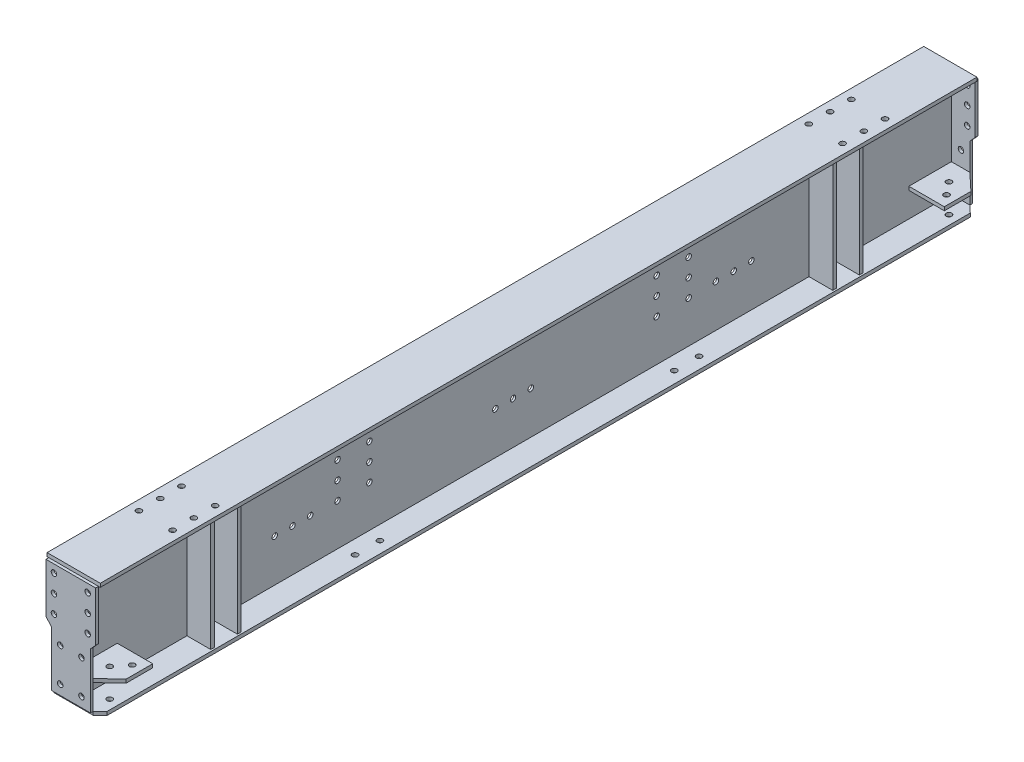
SolidWorks part; units mm, degrees
ref_plane "前视基准面" through (0, 0, 0) normal (0, 0, 1) x (1, 0, 0)
ref_plane "上视基准面" through (0, 0, 0) normal (0, 1, 0) x (1, 0, 0)
ref_plane "右视基准面" through (0, 0, 0) normal (1, 0, 0) x (0, 0, -1)
sketch "草图1" plane through (0, 0, 0) normal (0, 0, 1) x (1, 0, 0)
  line L0 (0, 0) -> (50000, 0) construction
  line L1 (0, 0) -> (0, 50000) construction
  line L2 (-150, 332.5) -> (150, 332.5)
  line L3 (150, 332.5) -> (150, 312.5)
  line L4 (150, 312.5) -> (6, 312.5)
  line L5 (6, 312.5) -> (6, -312.5)
  line L6 (6, -312.5) -> (150, -312.5)
  line L7 (150, -312.5) -> (150, -332.5)
  line L8 (150, -332.5) -> (-150, -332.5)
  line L9 (-150, -332.5) -> (-150, -312.5)
  line L10 (-150, -312.5) -> (-6, -312.5)
  line L11 (-6, -312.5) -> (-6, 312.5)
  line L12 (-6, 312.5) -> (-150, 312.5)
  line L13 (-150, 312.5) -> (-150, 332.5)
  dimension "D1" = 20
  dimension "D2" = 12
  dimension "D3" = 665
  dimension "D4" = 300
extrude "拉伸1" add sketch "草图1" along normal blind 2472
sketch "草图2" plane through (0, 0, 2472) normal (0, 0, 1) x (1, 0, 0)
  line L0 (-1000, 0) -> (49000, 0) construction
  line L1 (0, -1000) -> (0, 49000) construction
  line L2 (-140, 32.5) -> (-140, 312.5)
  line L3 (-150, 312.5) -> (-6, 312.5) construction
  line L4 (-140, 32.5) -> (-110, -0.5)
  line L5 (-140, 312.5) -> (140, 312.5)
  line L6 (-110, -0.5) -> (-110, -312.5)
  line L7 (-150, -332.5) -> (150, -332.5) construction
  line L8 (150, 332.5) -> (-150, 332.5) construction
  line L10 (-6, -312.5) -> (-150, -312.5) construction
  line L11 (-110, -312.5) -> (110, -312.5)
  line L12 (110, -0.5) -> (110, -312.5)
  line L13 (140, 32.5) -> (110, -0.5)
  line L14 (140, 32.5) -> (140, 312.5)
  point P7 (0, -312.5)
  point P18 (0, -332.5)
  point P21 (0, 332.5)
  point P23 (0, 312.5)
  dimension "D1" = 312
  dimension "D2" = 33
  dimension "D3" = 280
  dimension "D4" = 140
  dimension "D5" = 110
extrude "拉伸2" add sketch "草图2" along normal blind 16 separate body
sketch "草图3" plane through (0, 0, 2488) normal (0, 0, 1) x (1, 0, 0)
  line L0 (-1000, 0) -> (49000, 0) construction
  line L1 (0, -1000) -> (0, 49000) construction
  line L3 (-150, 312.5) -> (-6, 312.5) construction
  circle A0 centre (-95, 267.5) radius 15.5
  circle A1 centre (-95, 167.5) radius 15.5
  circle A2 centre (-95, 67.5) radius 15.5
  circle A3 centre (-60, -67.5) radius 15.5
  circle A4 centre (-60, -257.5) radius 15.5
  circle A5 centre (60, -257.5) radius 15.5
  circle A6 centre (60, -67.5) radius 15.5
  circle A7 centre (95, 67.5) radius 15.5
  circle A8 centre (95, 167.5) radius 15.5
  circle A9 centre (95, 267.5) radius 15.5
  dimension "D1" = 31
  dimension "D2" = 95
  dimension "D3" = 45
  dimension "D4" = 100
  dimension "D5" = 135
  dimension "D6" = 190
  dimension "D7" = 60
extrude "拉伸3" cut sketch "草图3" against normal through all
sketch "草图4" plane through (0, 332.5, 0) normal (0, 1, 0) x (1, 0, 0)
  line L0 (0, -1000) -> (0, 49000) construction
  line L1 (150, -2472) -> (-150, -2472) construction
  line L3 (-95, -2009) -> (-95, -1889) construction
  circle A0 centre (-95, -2009) radius 15.5
  circle A1 centre (-95, -1889) radius 15.5
  circle A2 centre (-95, -1769) radius 15.5
  circle A3 centre (95, -2009) radius 15.5
  circle A4 centre (95, -1889) radius 15.5
  circle A5 centre (95, -1769) radius 15.5
  dimension "D1" = 31
  dimension "D2" = 463
  dimension "D3" = 95
  dimension "D4" = 120
extrude "拉伸5" cut sketch "草图4" against normal blind 20
ref_plane "基准面1" through (0, -162.5, 0) normal (0, -1, 0) x (1, 0, 0)
sketch "草图6" plane through (0, -162.5, 0) normal (0, -1, 0) x (1, 0, 0)
  line L0 (0, -1000) -> (0, 49000) construction
  line L1 (-110, 2472) -> (-6, 2472)
  line L2 (-110, 2472) -> (-206, 2382)
  line L3 (-206, 2382) -> (-206, 2232)
  line L5 (-206, 2232) -> (-6, 2232)
  line L6 (-6, 2472) -> (-6, 0) construction
  line L7 (-6, 2232) -> (-6, 2472)
  line L8 (6, 2232) -> (6, 2472)
  line L9 (206, 2232) -> (6, 2232)
  line L10 (206, 2382) -> (206, 2232)
  line L11 (110, 2472) -> (206, 2382)
  line L12 (110, 2472) -> (6, 2472)
  dimension "D1" = 200
  dimension "D2" = 150
  dimension "D3" = 90
extrude "拉伸6" add sketch "草图6" along normal mid plane 20 separate body
sketch "草图7" plane through (0, -162.5, 0) normal (0, -1, 0) x (1, 0, 0)
  line L0 (0, -1000) -> (0, 49000) construction
  line L2 (-995.5174, 2488) -> (49004.4826, 2488) construction
  line L4 (-2000, 0) -> (-2000, 2488) construction
  line L6 (0, 2488) -> (-2362.8315, -451.3623) construction
  line L7 (-110, 2488) -> (110, 2488) construction
  circle A0 centre (-97.7382, 2366.4137) radius 15.5
  circle A1 centre (-154.1257, 2296.2677) radius 15.5
  circle A2 centre (154.1257, 2296.2677) radius 15.5
  circle A3 centre (97.7382, 2366.4137) radius 15.5
  dimension "D3" = 31
  dimension "D1" = 2488
  dimension "D2" = 2000
  dimension "D4" = 156
  dimension "D5" = 90
extrude "拉伸7" cut sketch "草图7" against normal mid plane 20
sketch "草图8" plane through (0, 312.5, 0) normal (0, -1, 0) x (1, 0, 0)
  line L0 (0, -1000) -> (0, 49000) construction
  line L1 (-95, 1889) -> (-95, 1769) construction
  line L2 (140, 1839) -> (-140, 1839)
  line L3 (-140, 1839) -> (-140, 1819)
  line L4 (-140, 1819) -> (140, 1819)
  line L5 (-1095, 1829) -> (48905, 1829) construction
  line L6 (140, 1839) -> (140, 1819)
  line L7 (140, 1689) -> (140, 1669)
  line L8 (-140, 1669) -> (140, 1669)
  line L9 (-140, 1689) -> (-140, 1669)
  line L10 (140, 1689) -> (-140, 1689)
  point P9 (0, 1839)
  point P14 (-95, 1829)
  point P16 (0, 1819)
  dimension "D1" = 140
  dimension "D2" = 20
  dimension "D3" = 150
  dimension "D4" = 20
  dimension "D5" = 280
extrude "拉伸8" add sketch "草图8" along normal blind 625
sketch "草图9" plane through (6, 0, 0) normal (1, 0, 0) x (0, 0, -1)
  line L0 (-2472, -332.5) -> (0, -332.5) construction
  line L2 (-900, -28.7712) -> (-900, -109.6678) construction
  line L3 (0, -312.5) -> (0, 312.5) construction
  line L4 (0, -88.5) -> (0, -58.5)
  line L5 (-2488, -312.5) -> (-2488, -0.5) construction
  circle A0 centre (-1344, -73.5) radius 15.5
  circle A1 centre (-1244, -73.5) radius 15.5
  circle A2 centre (-1144, -73.5) radius 15.5
  circle A3 centre (-990, -77.5) radius 15.5
  circle A4 centre (-990, 22.5) radius 15.5
  circle A5 centre (-990, 122.5) radius 15.5
  circle A6 centre (-810, 122.5) radius 15.5
  circle A7 centre (-810, 22.5) radius 15.5
  circle A8 centre (-810, -77.5) radius 15.5
  circle A9 centre (-100, -73.5) radius 15.5
  arc A10 (0, -58.5) -> (0, -88.5) centre (0, -73.5) ccw
  dimension "D1" = 31
  dimension "D5" = 31
  dimension "D10" = 31
  dimension "D13" = 15
  dimension "D2" = 259
  dimension "D3" = 1144
  dimension "D4" = 100
  dimension "D6" = 255
  dimension "D7" = 154
  dimension "D8" = 100
  dimension "D9" = 90
  dimension "D11" = 710
  dimension "D12" = 259
  dimension "D14" = 100
extrude "拉伸9" cut sketch "草图9" against normal blind 625
sketch "草图10" plane through (0, -312.5, 0) normal (0, 1, 0) x (1, 0, 0)
  line L1 (0, -1000) -> (0, 49000) construction
  line L2 (150, -2472) -> (150, 0) construction
  line L3 (-850, -900) -> (49150, -900) construction
  line L4 (150, 0) -> (-150, 0) construction
  line L6 (140, -2488) -> (-140, -2488) construction
  circle A0 centre (85, -970) radius 15.5
  circle A1 centre (85, -830) radius 15.5
  circle A2 centre (-85, -830) radius 15.5
  circle A3 centre (-85, -970) radius 15.5
  dimension "D1" = 31
  dimension "D2" = 1518
  dimension "D3" = 85
  dimension "D4" = 65
  dimension "D5" = 70
  dimension "D6" = 900
extrude "拉伸10" cut sketch "草图10" against normal blind 625
sketch "草图11" plane through (0, -312.5, 0) normal (0, 1, 0) x (1, 0, 0)
  line L0 (110, -2472) -> (150, -2472)
  line L3 (140, -2472) -> (-140, -2472) construction
  line L4 (150, -2472) -> (150, -2434.5)
  line L5 (150, -2434.5) -> (110, -2472)
  line L6 (-150, -2434.5) -> (-110, -2472)
  line L7 (-150, -2472) -> (-150, 0) construction
  line L8 (-110, -2472) -> (-206, -2382) construction
  line L9 (-110, -2472) -> (-150, -2472)
  line L10 (-150, -2472) -> (-150, -2434.5)
  line L11 (0, -1000) -> (0, 49000) construction
  circle A0 centre (-97.7382, -2366.4137) radius 15.5
  circle A1 centre (-97.7382, -2366.4137) radius 15.5 construction
  circle A2 centre (97.7382, -2366.4137) radius 15.5
extrude "拉伸11" cut sketch "草图11" against normal through all
mirror "镜向3" about plane through (0, 0, 0) normal (0, 0, 1) of bodies 128 112 114 117 104 110
mirror "镜向8" about plane through (0, 0, 0) normal (0, 0, 1) of bodies 104 117 110 114 118
